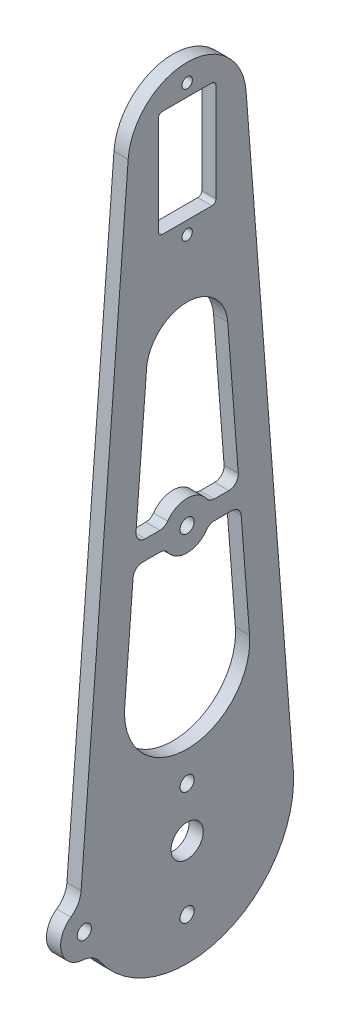
SolidWorks part; units mm, degrees
ref_plane "Front Plane" through (0, 0, 0) normal (0, 0, 1) x (1, 0, 0)
ref_plane "Top Plane" through (0, 0, 0) normal (0, 1, 0) x (1, 0, 0)
ref_plane "Right Plane" through (0, 0, 0) normal (1, 0, 0) x (0, 0, -1)
sketch "Sketch1" plane through (-22.7188, 0, 0) normal (1, 0, 0) x (0, 0, -1)
  line L0 (20.7893, 18.7887) -> (20.7893, 148.7887) construction
  line L1 (33.2523, 149.7503) -> (43.2226, 20.5195)
  line L2 (8.3264, 149.7503) -> (-1.644, 20.5195)
  arc A0 (-1.644, 20.5195) -> (43.2226, 20.5195) centre (20.7893, 18.7887) ccw
  arc A1 (33.2523, 149.7503) -> (8.3264, 149.7503) centre (20.7893, 148.7887) ccw
  dimension "D1" = 25
  dimension "D2" = 45
  dimension "D3" = 130
extrude "Boss-Extrude1" add sketch "Sketch1" along normal blind 3
sketch "Sketch2" plane through (-31.3188, -19.3399, 10.11) normal (1, 0, 0) x (0, -0.5157, -0.8568)
  line L0 (-60.2286, 159.9829) -> (6.8112, 48.6022) construction
  point P0 (-60.2286, 159.9829)
  line B0 (-49.4422, 143.1288) -> (-48.8247, 142.1029)
  line B1 (-47.2732, 148.6391) -> (-56.2694, 143.2244)
  line B2 (-57.436, 143.5143) -> (-54.9606, 139.4018)
  line B3 (-65.4549, 156.8372) -> (-57.436, 143.5143)
  line B4 (-46.9833, 149.8057) -> (-55.0023, 163.1286)
  line B5 (-63.3743, 165.2092) -> (-67.8724, 162.5018)
  line B6 (-68.1623, 161.3352) -> (-65.4549, 156.8372)
  line B7 (-55.0023, 163.1286) -> (-57.7097, 167.6267)
  line B8 (-58.8763, 167.9166) -> (-63.3743, 165.2092)
  line B9 (-61.3516, 172.0291) -> (-65.3784, 169.6053)
  line B10 (-65.7034, 168.0122) -> (-66.3209, 169.0381)
  line B11 (-70.6376, 165.4477) -> (-68.1623, 161.3352)
  line B12 (-57.7097, 167.6267) -> (-60.185, 171.7392)
  arc B13 (-55.0349, 156.7836) -> (-59.8328, 153.8957) centre (-60.2286, 159.9829) ccw
  arc B14 (-59.7397, 153.741) -> (-54.9418, 156.6289) centre (-57.3408, 155.1849) ccw
  arc B15 (-49.4422, 143.1288) -> (-50.3847, 142.5615) centre (-50.4047, 143.6613) ccw
  arc B16 (-47.2732, 148.6391) -> (-46.9833, 149.8057) centre (-47.7116, 149.3674) ccw
  arc B17 (-57.436, 143.5143) -> (-56.2694, 143.2244) centre (-56.7077, 143.9527) ccw
  arc B18 (-67.8724, 162.5018) -> (-68.1623, 161.3352) centre (-67.4341, 161.7736) ccw
  arc B19 (-57.7097, 167.6267) -> (-58.8763, 167.9166) centre (-58.4379, 167.1883) ccw
  arc B20 (-65.7034, 168.0122) -> (-64.7609, 168.5795) centre (-64.7409, 167.4797) ccw
sketch_block_instance "Servo 9g top-1"
sketch_block "Servo 9g top"
sketch "Sketch3" plane through (-19.7188, 0, 0) normal (1, 0, 0) x (0, 0, -1)
  line L0 (14.6893, 154.0387) -> (14.6893, 148.7887) construction
  line L1 (14.6893, 148.7887) -> (14.6893, 133.2387) construction
  line L2 (26.0393, 132.3887) -> (15.5393, 132.3887) construction
  line L3 (26.8893, 133.2387) -> (26.8893, 148.7887) construction
  line L4 (26.8893, 148.7887) -> (26.8893, 154.0387) construction
  line L5 (26.0393, 154.8887) -> (20.7893, 154.8887) construction
  line L6 (20.7893, 154.8887) -> (15.5393, 154.8887) construction
  line L7 (14.6893, 154.0387) -> (14.6893, 148.7887)
  line L8 (14.6893, 148.7887) -> (14.6893, 133.2387)
  line L9 (26.0393, 132.3887) -> (15.5393, 132.3887)
  line L10 (26.8893, 133.2387) -> (26.8893, 148.7887)
  line L11 (26.8893, 148.7887) -> (26.8893, 154.0387)
  line L12 (26.0393, 154.8887) -> (20.7893, 154.8887)
  line L13 (20.7893, 154.8887) -> (15.5393, 154.8887)
  arc A0 (15.5393, 154.8887) -> (14.6893, 154.0387) centre (15.5393, 154.0387) ccw construction
  arc A1 (14.6893, 133.2387) -> (15.5393, 132.3887) centre (15.5393, 133.2387) ccw construction
  arc A2 (26.0393, 132.3887) -> (26.8893, 133.2387) centre (26.0393, 133.2387) ccw construction
  arc A3 (26.8893, 154.0387) -> (26.0393, 154.8887) centre (26.0393, 154.0387) ccw construction
  arc A4 (15.5393, 154.8887) -> (14.6893, 154.0387) centre (15.5393, 154.0387) ccw
  arc A5 (14.6893, 133.2387) -> (15.5393, 132.3887) centre (15.5393, 133.2387) ccw
  arc A6 (26.0393, 132.3887) -> (26.8893, 133.2387) centre (26.0393, 133.2387) ccw
  arc A7 (26.8893, 154.0387) -> (26.0393, 154.8887) centre (26.0393, 154.0387) ccw
  circle A8 centre (20.7893, 157.5387) radius 1.1
  circle A9 centre (20.7893, 129.7387) radius 1.1
  arc A10 (21.3393, 128.7861) -> (20.2393, 128.7861) centre (20.7893, 129.7387) ccw construction
  arc A11 (20.2393, 158.4913) -> (21.3393, 158.4913) centre (20.7893, 157.5387) ccw construction
extrude "Cut-Extrude1" cut sketch "Sketch3" against normal up to next
sketch "Sketch4" plane through (-22.7188, 0, 0) normal (-1, 0, 0) x (0, 0, 1)
  line L0 (-20.7893, 18.7887) -> (-20.7893, 63.7491) construction
  point P5 (-20.7893, 18.7887)
sketch "Sketch5" plane through (-19.7188, 0, 0) normal (1, 0, 0) x (0, 0, -1)
  circle A0 centre (20.7893, 18.7887) radius 3.4 construction
  circle A1 centre (20.7893, 18.7887) radius 3.4
extrude "Cut-Extrude2" cut sketch "Sketch5" against normal up to next
sketch "Sketch6" plane through (-22.7188, 0, 0) normal (-1, 0, 0) x (0, 0, 1)
  line L0 (-20.7893, 18.7887) -> (-20.7893, 129.7387) construction
  line L1 (-12.2125, 109.4524) -> (-7.5972, 49.8096)
  line L2 (-43.2226, 20.5195) -> (-33.2523, 149.7503) construction
  line L3 (-20.7893, 108.7887) -> (-20.7893, 48.7887) construction
  line L4 (-29.3661, 109.4524) -> (-33.9814, 49.8096)
  arc A0 (-33.9814, 49.8096) -> (-7.5972, 49.8096) centre (-20.7893, 48.7887) ccw
  arc A1 (-12.2125, 109.4524) -> (-29.3661, 109.4524) centre (-20.7893, 108.7887) ccw
  point P8 (-29.3917, 108.7887)
  point P11 (-34.0208, 48.7887)
  dimension "D1" = 7
  dimension "D2" = 7
  dimension "D3" = 60
  dimension "D4" = 30
extrude "Cut-Extrude3" cut sketch "Sketch6" against normal up to next
sketch "Sketch7" plane through (-22.7188, 0, 0) normal (-1, 0, 0) x (0, 0, 1)
  line L0 (-20.7893, 35.5572) -> (-20.7893, 117.3911) construction
  line L1 (-31.918, 76.4742) -> (-9.6606, 76.4742) construction
  line L2 (-7.5972, 49.8096) -> (-12.2125, 109.4524) construction
  line L3 (-32.0728, 74.4742) -> (-25.3719, 74.4742)
  line L4 (-31.7633, 78.4742) -> (-25.3719, 78.4742)
  line L6 (-29.3661, 109.4524) -> (-33.9814, 49.8096) construction
  line L7 (-9.8154, 78.4742) -> (-9.5058, 74.4742)
  line L8 (-31.918, 78.4742) -> (-9.6606, 78.4742) construction
  line L9 (-31.7633, 78.4742) -> (-32.0728, 74.4742)
  line L10 (-31.918, 76.4742) -> (-9.6606, 76.4742) construction
  line L11 (-16.2067, 78.4742) -> (-9.8154, 78.4742)
  line L12 (-16.2067, 74.4742) -> (-9.5058, 74.4742)
  arc A0 (-33.9814, 49.8096) -> (-7.5972, 49.8096) centre (-20.7893, 48.7887) ccw construction
  arc A1 (-12.2125, 109.4524) -> (-29.3661, 109.4524) centre (-20.7893, 108.7887) ccw construction
  arc A2 (-16.2067, 78.4742) -> (-25.3719, 78.4742) centre (-20.7893, 76.4742) ccw
  arc A3 (-25.3719, 74.4742) -> (-16.2067, 74.4742) centre (-20.7893, 76.4742) ccw
  circle A4 centre (-20.7893, 76.4742) radius 1.5
  point P15 (-20.7893, 76.4742)
  dimension "D1" = 10
  dimension "D4" = 3
  dimension "D2" = 2
  dimension "D3" = 2
extrude "Boss-Extrude3" add sketch "Sketch7" against normal up to surface (3 mm away) up to face at (-19.7188, 78.0526, -20.7893)
fillet "Fillet1" radius 2 8 edges at (-21.2188, 78.4742, -16.2067) (-21.2188, 78.4742, -25.3719) (-21.2188, 78.4742, -9.8154) (-21.2188, 74.4742, -25.3719) (-21.2188, 74.4742, -16.2067) (-21.2188, 74.4742, -9.5058) (-21.2188, 74.4742, -32.0728) (-21.2188, 78.4742, -31.7633)
sketch "Sketch8" plane through (-22.7188, 0, 0) normal (-1, 0, 0) x (0, 0, 1)
  line L0 (-20.7893, 18.7887) -> (0.944, 12.9653) construction
  arc A2 (-43.2226, 20.5195) -> (1.644, 20.5195) centre (-20.7893, 18.7887) ccw construction
  circle A3 centre (0.944, 12.9653) radius 5
  dimension "D2" = 10
  dimension "D1" = 15
extrude "Boss-Extrude4" add sketch "Sketch8" against normal up to surface (3 mm away) up to face at (-19.7188, 86.1528, -20.7893)
sketch "Sketch9" plane through (-22.7188, 0, 0) normal (-1, 0, 0) x (0, 0, 1)
  circle A1 centre (0.944, 12.9653) radius 1.5
  dimension "D1" = 3
extrude "Cut-Extrude4" cut sketch "Sketch9" against normal up to next
fillet "Fillet2" radius 5 2 edges at (-21.2188, 17.9088, 1.6935) (-21.2188, 8.3094, -0.8787)
sketch "Sketch10" plane through (-22.7188, 0, 0) normal (-1, 0, 0) x (0, 0, 1)
  circle A0 centre (-20.7893, 29.2887) radius 1.5
  circle A1 centre (-20.7893, 5.2887) radius 1.5
  dimension "D1" = 3
extrude "Cut-Extrude5" cut sketch "Sketch10" against normal up to next
